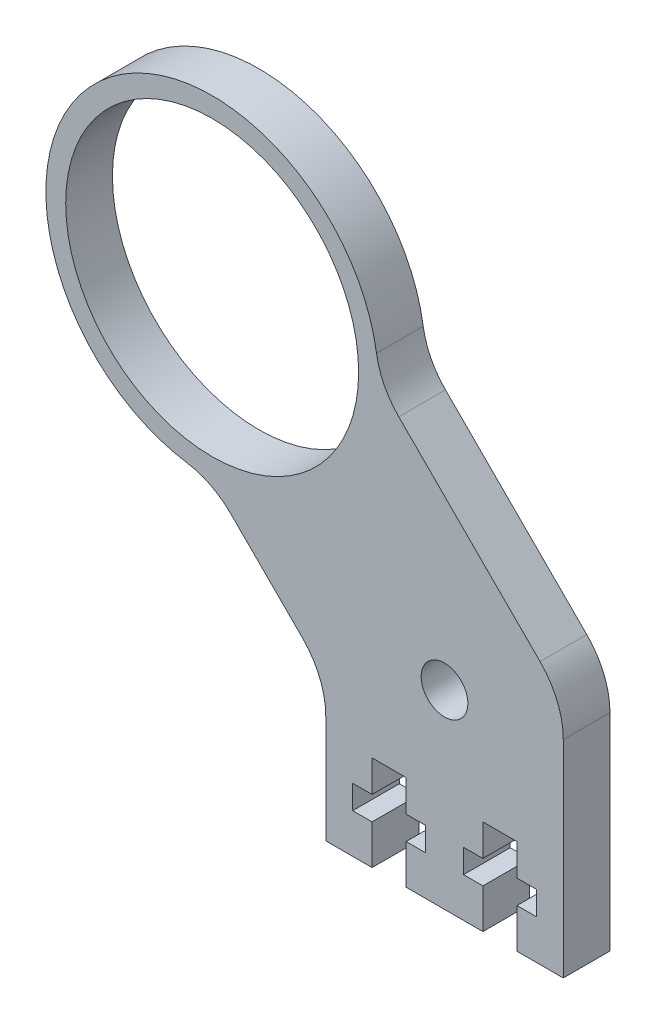
SolidWorks part; units mm, degrees
ref_plane "Front Plane" through (0, 0, 0) normal (0, 0, 1) x (1, 0, 0)
ref_plane "Top Plane" through (0, 0, 0) normal (0, 1, 0) x (1, 0, 0)
ref_plane "Right Plane" through (0, 0, 0) normal (1, 0, 0) x (0, 0, -1)
sketch "Sketch1" plane through (0, 0, 0) normal (0, 0, 1) x (1, 0, 0)
  line L0 (0, 0) -> (-29.3449, 29.3449) construction
  line L1 (0, 0) -> (0, 31.0325) construction
  line L2 (-15, -6.2132) -> (-15, -24)
  line L3 (-15, -24) -> (15, -24)
  line L4 (15, -24) -> (15, 6.2132)
  line L5 (0, 0) -> (0, -24) construction
  line L6 (15, 6.2132) -> (-8.346, 29.5592)
  line L7 (-15, -6.2132) -> (-29.5592, 8.346)
  line L8 (10.6066, 10.6066) -> (-18.7383, 39.9515) construction
  line L9 (-10.6066, -10.6066) -> (-39.9515, 18.7383) construction
  circle A0 centre (0, 0) radius 2.95
  arc A1 (-8.346, 29.5592) -> (-29.5592, 8.346) centre (-29.3449, 29.3449) ccw
  dimension "D1" = 5.9
  dimension "D3" = 42
  dimension "D2" = 41.5
  dimension "D4" = 45
  dimension "D5" = 24
  dimension "D6" = 30
  dimension "D7" = 15
  dimension "D8" = 15
extrude "Boss-Extrude1" add sketch "Sketch1" along normal blind 5.9
sketch "Sketch2" plane through (0, 0, 5.9) normal (0, 0, 1) x (1, 0, 0)
  circle A0 centre (-29.3449, 29.3449) radius 18.5
  dimension "D1" = 37
extrude "Cut-Extrude1" cut sketch "Sketch2" against normal through all
sketch "Sketch3" plane through (0, 0, 5.9) normal (0, 0, 1) x (1, 0, 0)
  line L0 (-15, -24) -> (15, -24) construction
  line L1 (-9.15, -24) -> (-4.85, -24)
  line L2 (-9.15, -24) -> (-9.15, -19)
  line L3 (-9.15, -12) -> (-4.85, -12)
  line L4 (-4.85, -24) -> (-4.85, -19)
  line L5 (0, 0) -> (0, -24) construction
  line L6 (-4.85, -16) -> (-2.4, -16)
  line L7 (-11.6, -16) -> (-9.15, -16)
  line L8 (-11.6, -16) -> (-11.6, -19)
  line L9 (-11.6, -19) -> (-9.15, -19)
  line L10 (-2.4, -16) -> (-2.4, -19)
  line L11 (-9.15, -16) -> (-9.15, -12)
  line L12 (-4.85, -19) -> (-2.4, -19)
  line L13 (-4.85, -16) -> (-4.85, -12)
  line L14 (4.85, -16) -> (4.85, -12)
  line L15 (4.85, -19) -> (2.4, -19)
  line L16 (9.15, -16) -> (9.15, -12)
  line L17 (2.4, -16) -> (2.4, -19)
  line L18 (11.6, -19) -> (9.15, -19)
  line L19 (11.6, -16) -> (11.6, -19)
  line L20 (11.6, -16) -> (9.15, -16)
  line L21 (4.85, -16) -> (2.4, -16)
  line L22 (4.85, -24) -> (4.85, -19)
  line L23 (9.15, -12) -> (4.85, -12)
  line L24 (9.15, -24) -> (9.15, -19)
  line L25 (9.15, -24) -> (4.85, -24)
  point P6 (-7, -12)
  point P18 (-10.375, -19)
  dimension "D1" = 4.3
  dimension "D2" = 7
  dimension "D3" = 12
  dimension "D4" = 9.2
  dimension "D5" = 3
  dimension "D6" = 5
extrude "Cut-Extrude2" cut sketch "Sketch3" against normal through all
fillet "Fillet1" radius 10 4 edges at (-8.346, 29.5592, 2.95) (15, 6.2132, 2.95) (-15, -6.2132, 2.95) (-29.5592, 8.346, 2.95)
equation "\"smallPulleyTeeth\"= 15"
equation "\"largePulleyTeeth\"= 40"
equation "\"eighthThick\"= 2.9mm"
equation "\"sixteenthThick\" = 1.7mm"
equation "\"quarterThick\"=5.9mm"
equation "\"OD\" = 145mm"
equation "\"puckAngle\" = 60.5deg"
equation "\"puckDiam\" = 76.5mm"
equation "\"axlePress\" = 5.9mm"
equation "\"D1@Sketch1\"=\"axlePress\""
equation "\"D1@Boss-Extrude1\"=\"quarterThick\""
equation "\"press\" = 0.2mm"
equation "\"wheelClear\" = 0.3mm"
equation "\"10-32clear\" = 4.5mm"
equation "\"D1@Sketch3\"=\"10-32clear\"-\"press\""
equation "\"6-32clear\" = 3.3mm"
equation "\"8-32clear\" = 4.0mm"
equation "\"wheelHeight\" = 24mm"
equation "\"D5@Sketch1\"=\"wheelHeight\""
